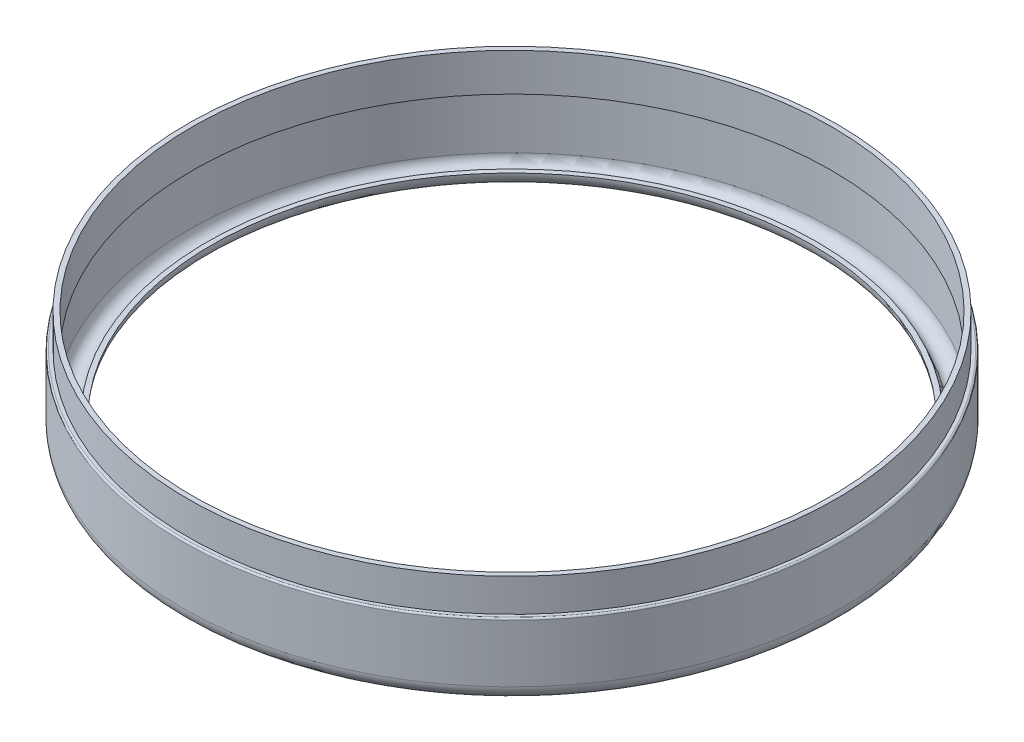
SolidWorks part; units mm, degrees
material "PC High Viscosity"
ref_plane "Front Plane" through (0, 0, 0) normal (1, 0, 0) x (0, 1, 0)
ref_plane "Top Plane" through (0, 0, 0) normal (0, 0, 1) x (0, 1, 0)
ref_plane "Right Plane" through (0, 0, 0) normal (0, 1, 0) x (-1, 0, 0)
sketch "Sketch1" plane through (0, 0, 0) normal (1, 0, 0) x (0, 1, 0)
  line L0 (-178.1369, 0) -> (271.2391, 0) construction
  line L1 (0, 175.9662) -> (0, -160.8293) construction
  line L2 (-9, 100) -> (9, 100)
  line L3 (9, 100) -> (9, 98.5)
  line L4 (9, 98.5) -> (19, 98.5)
  line L5 (-9, 98.5) -> (7.5, 98.5)
  line L6 (7.5, 98.5) -> (7.5, 97)
  line L7 (7.5, 97) -> (19, 97)
  line L8 (-9, 92.5) -> (-9, 91)
  line L9 (19, 98.5) -> (19, 97)
  arc A0 (-9, 100) -> (-9, 91) centre (-9, 95.5) ccw
  arc A1 (-9, 98.5) -> (-9, 92.5) centre (-9, 95.5) ccw
  arc A2 (-9, 100) -> (-10.1112, 91.1393) centre (-9, 95.5) ccw construction
  arc A3 (-9, 98.5) -> (-9.7408, 92.5929) centre (-9, 95.5) ccw construction
  point P12 (0, 100)
  dimension "D2" = 4.5
  dimension "D1" = 100
  dimension "D3" = 18
  dimension "D4" = 10
  dimension "D6" = 97
  dimension "D5" = 1.5
revolve "Revolve1" add sketch "Sketch1" angle 360 about L0
fillet "Fillet1" radius 0.5 1 edges at (0, 9, -100)
